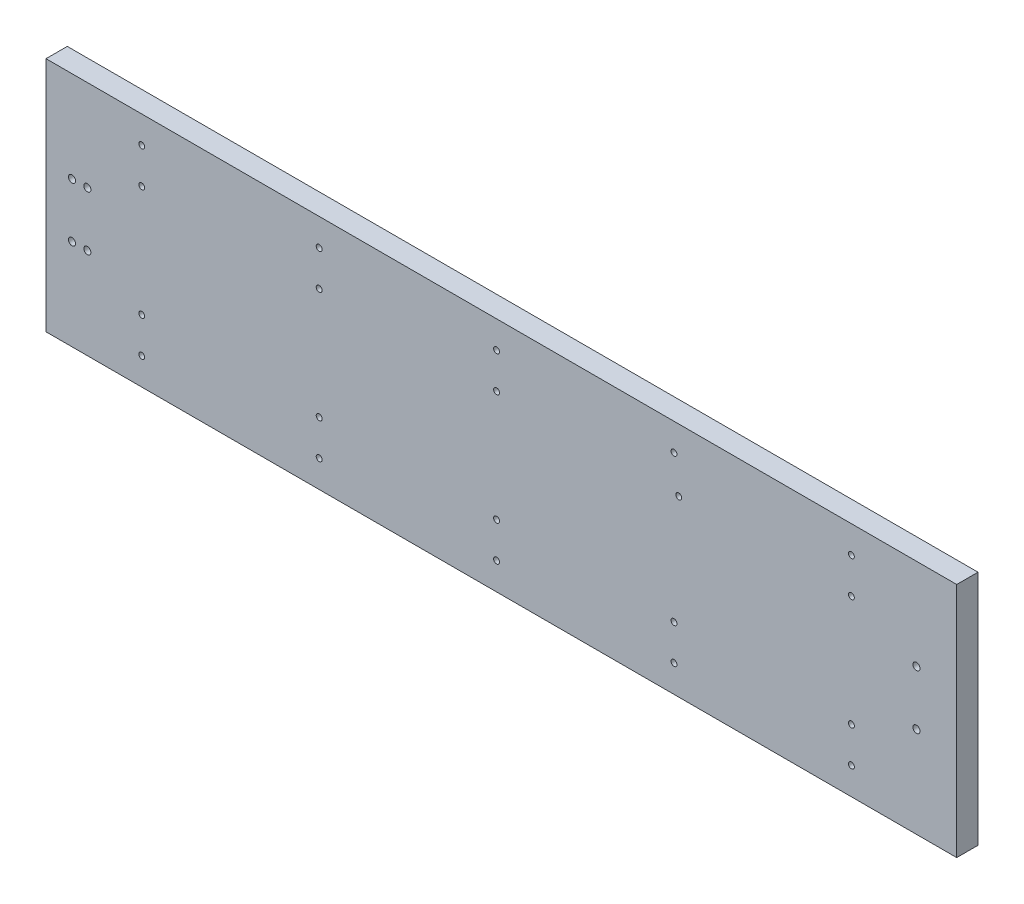
SolidWorks part; units mm, degrees
ref_plane "Front Plane" through (0, 0, 0) normal (0, 0, 1) x (1, 0, 0)
ref_plane "Top Plane" through (0, 0, 0) normal (0, 1, 0) x (1, 0, 0)
ref_plane "Right Plane" through (0, 0, 0) normal (1, 0, 0) x (0, 0, -1)
sketch "Sketch1" plane through (0, 0, 0) normal (0, 0, 1) x (1, 0, 0)
  line L1 (-385, 100) -> (385, 100)
  line L2 (-385, 100) -> (-385, -100)
  line L3 (-385, -100) -> (385, -100)
  line L4 (385, 100) -> (385, -100)
  line L5 (-385, 100) -> (385, -100) construction
  line L6 (-385, -100) -> (385, 100) construction
  point P0 (0, 0)
  dimension "D1" = 770
  dimension "D2" = 200
extrude "Boss-Extrude1" add sketch "Sketch1" along normal blind 18
hole_wizard "Ø5.0 (5) Diameter Hole5" positions "Sketch17" profile "Sketch16" hole size "Ø5.0" standard "ISO" end condition through all
sketch "Sketch17" plane through (0, 0, 0) normal (0, 0, -1) x (-1, 0, 0)
  point P0 (-295.9601, 77)
  point P3 (-295.9601, 47)
  point P6 (-145.9601, 77)
  point P9 (-150, 47)
  point P11 (4.0399, 77)
  point P14 (4.0399, 47)
  point P17 (154.0399, 77)
  point P20 (154.0399, 47)
  point P23 (304.0399, 77)
  point P26 (304.0399, 47)
  point P29 (304.0399, -47)
  point P32 (304.0399, -77)
  point P35 (154.0399, -77)
  point P38 (154.0399, -47)
  point P41 (4.0399, -47)
  point P44 (4.0399, -77)
  point P47 (-145.9601, -77)
  point P50 (-145.9601, -47)
  point P53 (-295.9601, -47)
  point P56 (-295.9601, -77)
sketch "Sketch16" plane through (295.9601, 77, 0) normal (1, 0, 0) x (0, 1, 0)
  line L0 (0, 0) -> (0, 18)
  line L1 (0, 18) -> (2.5, 18)
  line L2 (2.5, 18) -> (2.5, 0)
  line L5 (2.5, 0) -> (0, 0)
  line L11 (0, -6.35) -> (0, 107.95) construction
  dimension "Thru Hole Dia." = 5
  dimension "Thru Hole Depth" = 18
hole_wizard "Ø6.0 (6) Diameter Hole2" positions "Sketch19" profile "Sketch18" hole size "Ø6.0" standard "ISO" end condition through all
sketch "Sketch19" plane through (0, 0, 0) normal (0, 0, -1) x (-1, 0, 0)
  point P0 (-350.9608, 23)
  point P3 (-350.9608, -23)
  point P6 (350.0392, 23)
  point P9 (363.0392, 23)
  point P12 (350.0392, -23)
  point P15 (363.0392, -23)
sketch "Sketch18" plane through (350.9608, 23, 0) normal (1, 0, 0) x (0, 1, 0)
  line L0 (0, 0) -> (0, 18)
  line L1 (0, 18) -> (3, 18)
  line L2 (3, 18) -> (3, 0)
  line L5 (3, 0) -> (0, 0)
  line L11 (0, -6.35) -> (0, 107.95) construction
  dimension "Thru Hole Dia." = 6
  dimension "Thru Hole Depth" = 18
